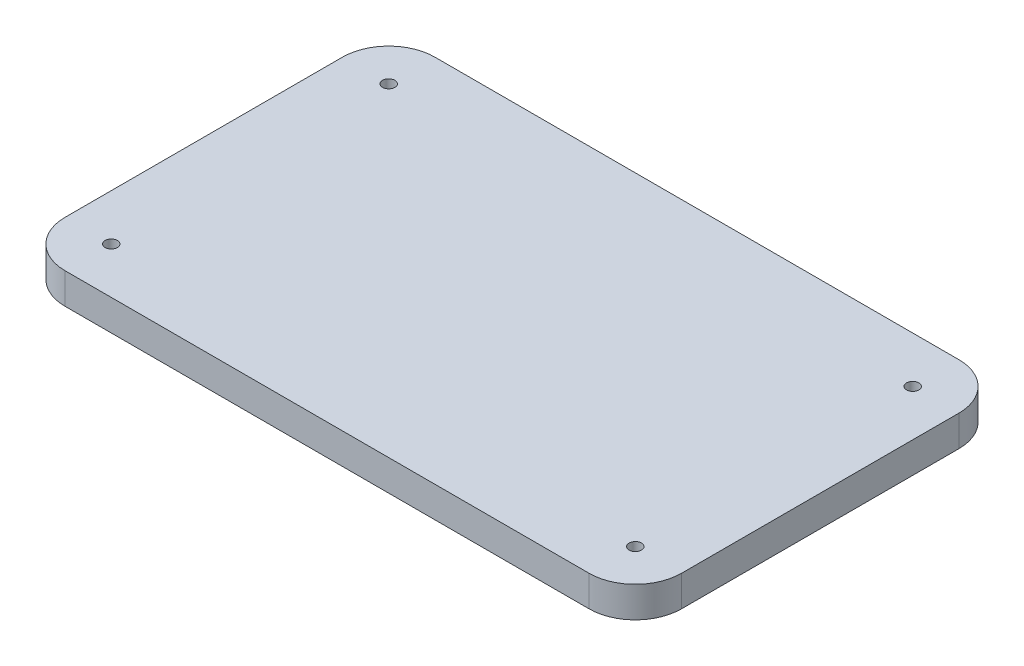
SolidWorks part; units mm, degrees
material "Acrylic (Medium-high impact)"
ref_plane "Front Plane" through (0, 0, 0) normal (0, 0, 1) x (1, 0, 0)
ref_plane "Top Plane" through (0, 0, 0) normal (0, 1, 0) x (1, 0, 0)
ref_plane "Right Plane" through (0, 0, 0) normal (1, 0, 0) x (0, 0, -1)
sketch "Sketch1" plane through (0, 0, 0) normal (0, 1, 0) x (1, 0, 0)
  line L0 (-55, 0) -> (55, 0) construction
  line L1 (53.975, 28.575) -> (-53.975, -28.575) construction
  line L2 (53.975, -28.575) -> (-53.975, 28.575) construction
  line L4 (63.5, -28.575) -> (63.5, 28.575)
  line L5 (-53.975, -38.1) -> (53.975, -38.1)
  line L6 (-63.5, 28.575) -> (-63.5, -28.575)
  line L7 (53.975, 38.1) -> (-53.975, 38.1)
  arc A4 (63.5, 28.575) -> (53.975, 38.1) centre (53.975, 28.575) ccw
  arc A5 (53.975, -38.1) -> (63.5, -28.575) centre (53.975, -28.575) ccw
  arc A6 (-63.5, -28.575) -> (-53.975, -38.1) centre (-53.975, -28.575) ccw
  arc A7 (-53.975, 38.1) -> (-63.5, 28.575) centre (-53.975, 28.575) ccw
  point P4 (56.5549, -23.9732)
  point P7 (0, 0)
  point P9 (0, 0)
  dimension "D3" = 9.525
  dimension "D1" = 107.95
  dimension "D2" = 57.15
extrude "Boss-Extrude1" add sketch "Sketch1" along normal blind 6.35
hole_wizard "#6-40 Tapped Hole2" positions "3DSketch2" profile "Sketch3" tap size "#6-40" standard "ANSI Inch"
sketch3d "3DSketch2"
  arc A3 (-53.975, 6.35, -38.1) -> (-63.5, 6.35, -28.575) centre (-53.975, 6.35, -28.575) ccw construction
  arc A4 (63.5, 6.35, -28.575) -> (53.975, 6.35, -38.1) centre (53.975, 6.35, -28.575) ccw construction
  arc A5 (53.975, 6.35, 38.1) -> (63.5, 6.35, 28.575) centre (53.975, 6.35, 28.575) ccw construction
  arc A6 (-63.5, 6.35, 28.575) -> (-53.975, 6.35, 38.1) centre (-53.975, 6.35, 28.575) ccw construction
  point P21 (53.975, 6.35, -28.575)
  point P23 (53.975, 6.35, 28.575)
  point P25 (-53.975, 6.35, -28.575)
  point P27 (-53.975, 6.35, 28.575)
  point P30 (0, 0, 0)
  point P31 (0, 0, 0)
  point P32 (0, 0, 0)
  point P36 (-53.975, 15.875, -28.575)
  point P37 (0, 0, 0)
  point P41 (53.975, 15.875, -28.575)
  point P42 (0, 0, 0)
  point P46 (53.975, 15.875, 28.575)
  point P47 (0, 0, 0)
  point P51 (-53.975, 15.875, 28.575)
sketch "Sketch3" plane through (53.975, 6.35, -28.575) normal (1, 0, 0) x (0, 0, 1)
  line L0 (0, 0) -> (0, 9.6785)
  line L1 (0, 9.6785) -> (1.27, 8.9154)
  line L2 (1.27, 8.9154) -> (1.27, 0)
  line L5 (1.27, 0) -> (0, 0)
  line L10 (0, 9.6785) -> (-1.27, 8.9154) construction
  line L11 (0, -6.35) -> (0, 107.95) construction
  dimension "Tap Drill Dia." = 2.54
  dimension "Tap Drill Depth" = 8.9154
  dimension "Drill Angle" = 118
cosmetic thread "Hole Thread1" parameters "D1"=6.35, "D2"=3.5052
cosmetic thread "Hole Thread2" parameters "D1"=6.35, "D2"=3.5052
cosmetic thread "Hole Thread3" parameters "D1"=6.35, "D2"=3.5052
cosmetic thread "Hole Thread4" parameters "D1"=6.35, "D2"=3.5052
